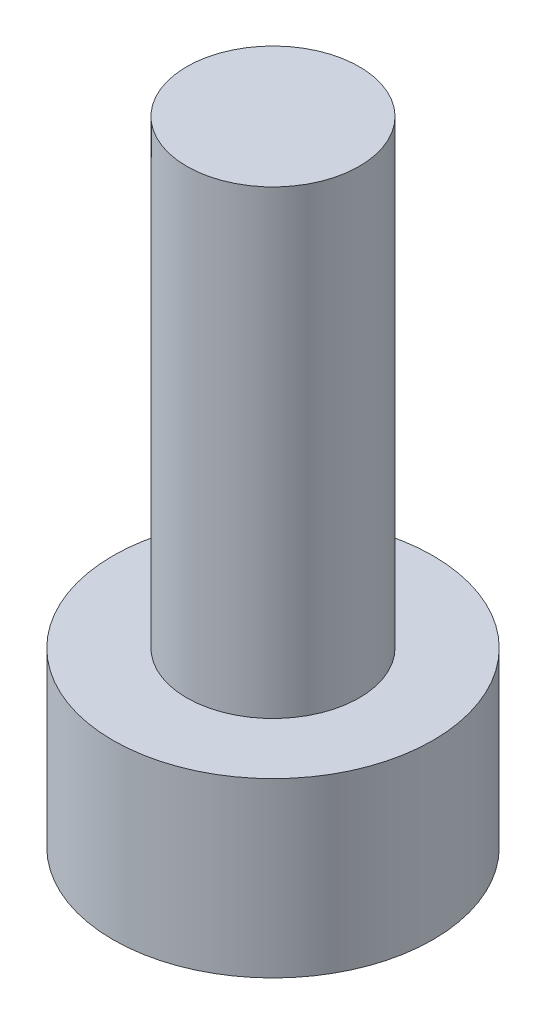
SolidWorks part; units mm, degrees
ref_plane "Front Plane" through (0, 0, 0) normal (0, 0, 1) x (1, 0, 0)
ref_plane "Top Plane" through (0, 0, 0) normal (0, 1, 0) x (1, 0, 0)
ref_plane "Right Plane" through (0, 0, 0) normal (1, 0, 0) x (0, 0, -1)
sketch "Sketch1" plane through (0, 0, 0) normal (0, 1, 0) x (1, 0, 0)
  circle A0 centre (0, 0) radius 2.78
  dimension "D1" = 5.56
extrude "Boss-Extrude1" add sketch "Sketch1" along normal blind 3
sketch "Sketch2" plane through (0, 3, 0) normal (0, 1, 0) x (1, 0, 0)
  circle A0 centre (0, 0) radius 1.5
  dimension "D1" = 3
extrude "Boss-Extrude2" add sketch "Sketch2" along normal blind 8
